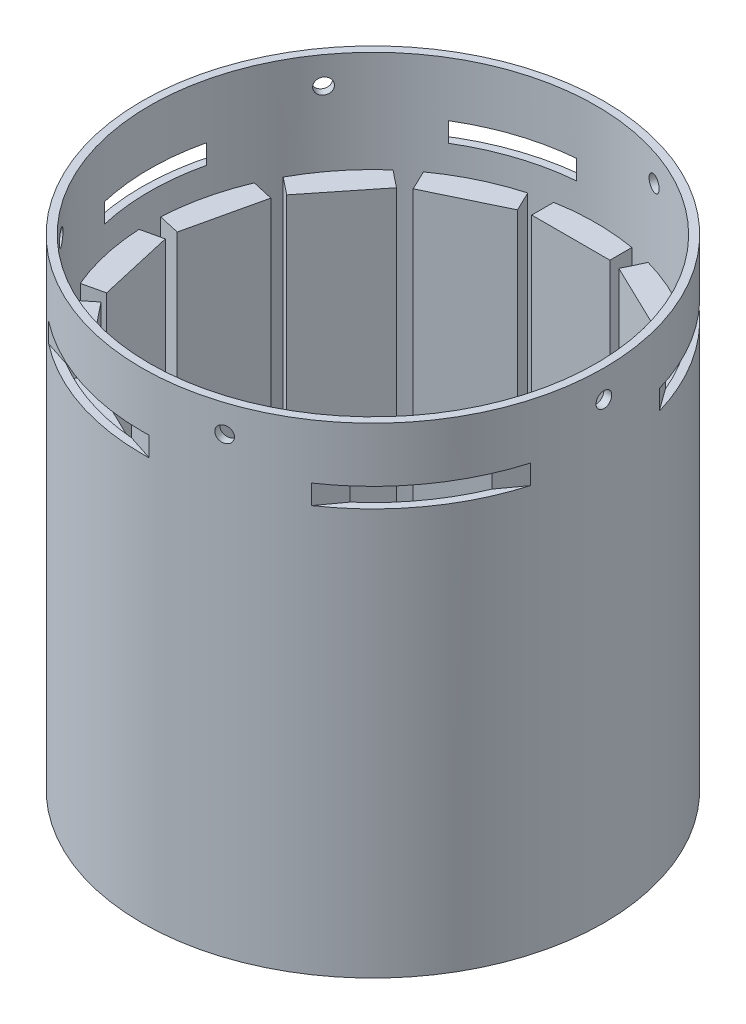
SolidWorks part; units mm, degrees
ref_plane "Front Plane" through (0, 0, 0) normal (0, 0, 1) x (1, 0, 0)
ref_plane "Top Plane" through (0, 0, 0) normal (0, 1, 0) x (1, 0, 0)
ref_plane "Right Plane" through (0, 0, 0) normal (1, 0, 0) x (0, 0, -1)
sketch "Sketch1" plane through (0, 0, 0) normal (0, 1, 0) x (1, 0, 0)
  circle A0 centre (0, 0) radius 29.575
  circle A1 centre (0, 0) radius 28.575
  dimension "D1" = 59.15
  dimension "D2" = 1
extrude "Boss-Extrude1" add sketch "Sketch1" along normal blind 61.5
ref_plane "Plane1" through (0, 4.5, 0) normal (0, -1, 0) x (-1, 0, 0)
sketch "Sketch2" plane through (0, 4.5, 0) normal (0, -1, 0) x (-1, 0, 0)
  line L0 (0, 0) -> (0, 32.3622) construction
  line L1 (-5, 25.325) -> (-5, 28.575)
  line L2 (-5, 25.325) -> (5, 25.325)
  line L3 (-5, 28.575) -> (5, 28.575)
  line L4 (5, 25.325) -> (5, 28.575)
  line L5 (-5, 25.325) -> (5, 28.575) construction
  line L6 (-5, 28.575) -> (5, 25.325) construction
  circle A0 centre (0, 0) radius 28.575 construction
  circle A1 centre (0, 0) radius 28.575
  point P4 (0, 28.575)
  point P6 (0, 26.95)
  dimension "D1" = 3.25
  dimension "D2" = 0
  dimension "D3" = 10
  dimension "D4" = 5
extrude "Boss-Extrude2" add sketch "Sketch2" against normal blind 44 and the other way blind 2.5 contours A1 L1 L2 L4 | A1 L4 L3
sketch "Sketch3" plane through (0, 0, 0) normal (0, 0, 1) x (1, 0, 0)
  line L0 (0, 0) -> (0, 57.7625) construction
pattern_circular "CirPattern1" count 14 over 360 about axis through (0, 0, 0) along (0, 1, 0) of "Boss-Extrude2"
ref_plane "Plane2" through (0, 0, 29.575) normal (0, 0, 1) x (1, 0, 0)
sketch "Sketch4" plane through (0, 0, 29.575) normal (0, 0, 1) x (1, 0, 0)
  line L0 (-29.575, 0) -> (29.575, 0) construction
  line L1 (-29.575, 0) -> (29.575, 0)
  line L2 (-29.575, 0) -> (-29.575, 60.8021) construction
  line L3 (28.575, 61.5) -> (-28.575, 61.5) construction
  line L4 (-29.575, 54.5) -> (-27.825, 54.5)
  line L5 (-29.575, 54.5) -> (-29.575, 52)
  line L6 (-29.575, 52) -> (-27.825, 52)
  line L7 (-27.825, 54.5) -> (-27.825, 52)
  dimension "D1" = 7
  dimension "D2" = 2.5
  dimension "D3" = 1.75
extrude "Cut-Extrude1" cut sketch "Sketch4" against normal through all contours L7 L4 L5 L6
pattern_circular "CirPattern2" count 5 over 360 about axis through (0, 0, 0) along (0, 1, 0) of "Cut-Extrude1"
ref_plane "Plane3" through (8.7767, 0, 27.0119) normal (-0.309, 0, -0.9511) x (-0.9511, 0, 0.309)
sketch "Sketch5" plane through (8.7767, 0, 27.0119) normal (-0.309, 0, -0.9511) x (-0.9511, 0, 0.309)
  line L0 (29.575, 61.5) -> (-29.575, 61.5) construction
  circle A0 centre (0, 58) radius 1
  dimension "D1" = 3.5
extrude "Cut-Extrude2" cut sketch "Sketch5" against normal blind 5 and the other way blind 5
pattern_circular "CirPattern3" count 5 over 360 about axis through (0, 0, 0) along (0, 1, 0) of "Cut-Extrude2"
